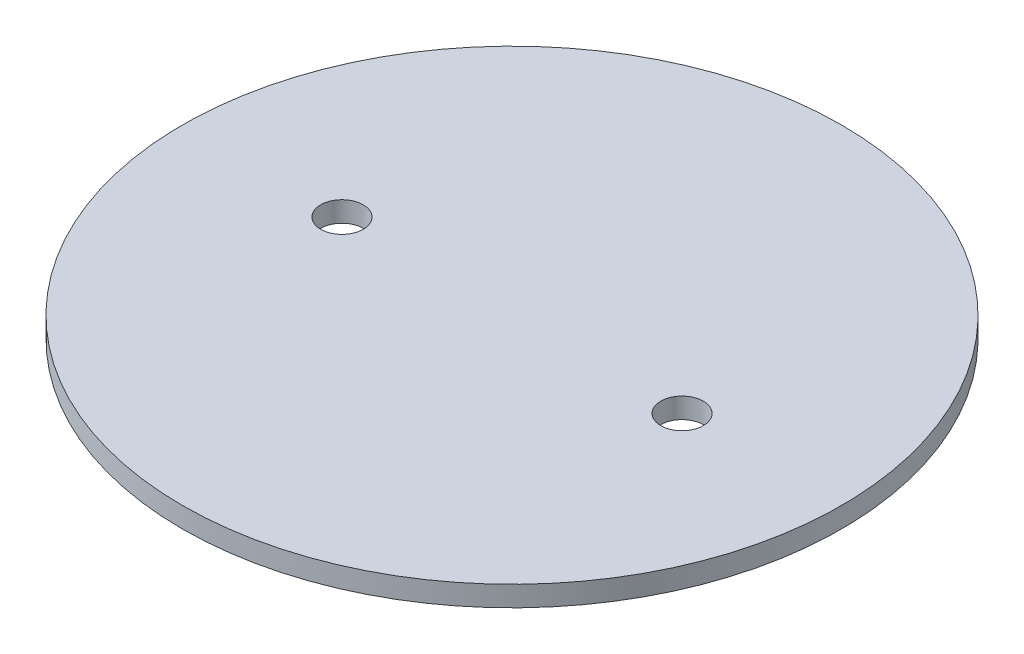
SolidWorks part; units mm, degrees
ref_plane "Front Plane" through (0, 0, 0) normal (0, 0, 1) x (1, 0, 0)
ref_plane "Top Plane" through (0, 0, 0) normal (0, 1, 0) x (1, 0, 0)
ref_plane "Right Plane" through (0, 0, 0) normal (1, 0, 0) x (0, 0, -1)
sketch "Sketch1" plane through (0, 0, 0) normal (0, 1, 0) x (1, 0, 0)
  line L0 (0, 0) -> (-50000, 0) construction
  circle A0 centre (0, 0) radius 96.9
  circle A1 centre (-50, 0) radius 6.25
  circle A2 centre (50, 0) radius 6.25
  dimension "D1" = 193.8
  dimension "D2" = 12.5
  dimension "D3" = 12.5
  dimension "D5" = 100
extrude "Boss-Extrude1" add sketch "Sketch1" along normal mid plane 6
